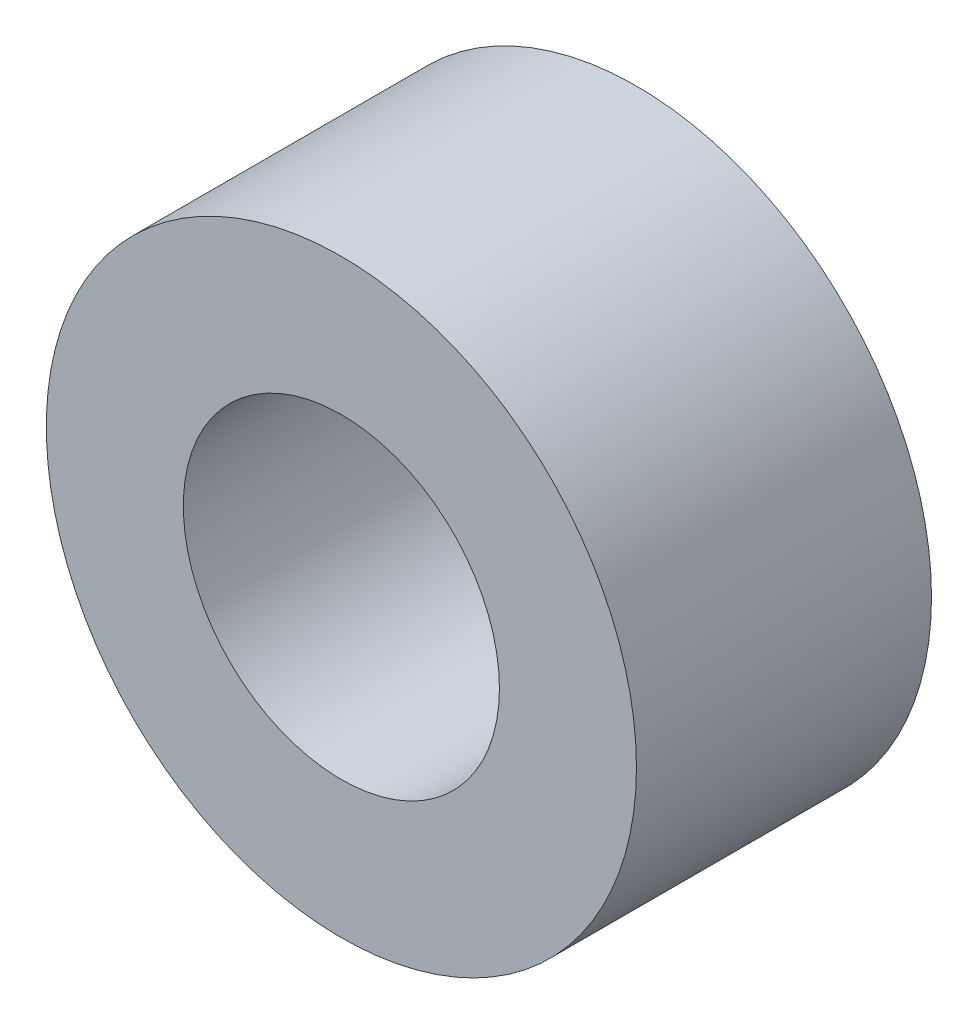
SolidWorks part; units mm, degrees
material "PET"
ref_plane "Front Plane" through (0, 0, 0) normal (0, 0, 1) x (1, 0, 0)
ref_plane "Top Plane" through (0, 0, 0) normal (0, 1, 0) x (1, 0, 0)
ref_plane "Right Plane" through (0, 0, 0) normal (1, 0, 0) x (0, 0, -1)
sketch "Sketch1" plane through (0, 0, 0) normal (0, 0, 1) x (1, 0, 0)
  circle A0 centre (0, 0) radius 4.7625
  circle A1 centre (0, 0) radius 8.89
  point P5 (0, 0)
  dimension "D1" = 17.78
  dimension "D2" = 9.525
extrude "Boss-Extrude1" add sketch "Sketch1" along normal mid plane 8.89
